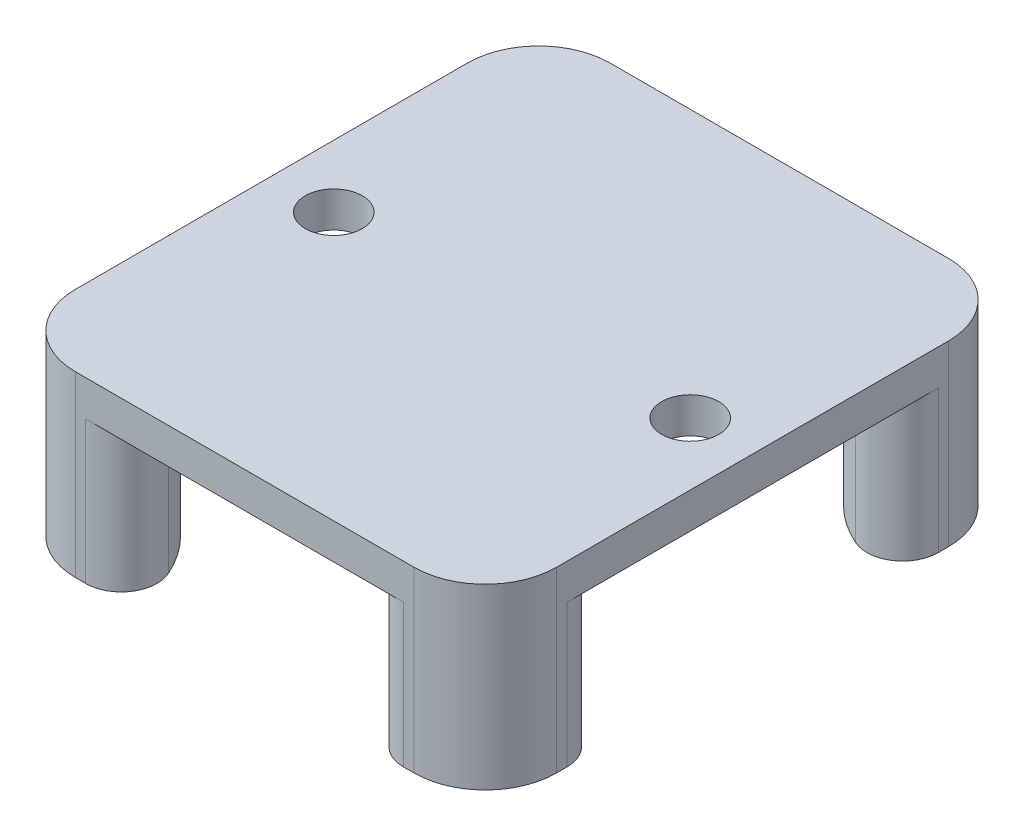
SolidWorks part; units mm, degrees
ref_plane "Płaszczyzna przednia" through (0, 0, 0) normal (0, 0, 1) x (1, 0, 0)
ref_plane "Płaszczyzna górna" through (0, 0, 0) normal (0, 1, 0) x (1, 0, 0)
ref_plane "Płaszczyzna prawa" through (0, 0, 0) normal (1, 0, 0) x (0, 0, -1)
sketch "Szkic1" plane through (0, 0, 0) normal (0, 1, 0) x (1, 0, 0)
  line L0 (-10, 0) -> (10, 0) construction
  line L2 (-13.5, -15) -> (13.5, -15)
  line L3 (-13.5, -15) -> (-13.5, 15)
  line L4 (-13.5, 15) -> (13.5, 15)
  line L5 (13.5, -15) -> (13.5, 15)
  line L6 (-13.5, -15) -> (13.5, 15) construction
  line L7 (-13.5, 15) -> (13.5, -15) construction
  circle A0 centre (10, 0) radius 1.6
  circle A1 centre (-10, 0) radius 1.6
  point P4 (0, 0)
  point P7 (0, 0)
  dimension "D1" = 3.2
  dimension "D2" = 3.2
  dimension "D3" = 27
  dimension "D4" = 30
  dimension "D5" = 20
extrude "Dodanie-wyciągnięcie1" add sketch "Szkic1" along normal blind 2
sketch "Szkic2" plane through (0, 0, 0) normal (0, -1, 0) x (1, 0, 0)
  line L0 (-13.5, 15) -> (13.5, 15) construction
  line L1 (-13.5, -15) -> (-13.5, 15) construction
  line L2 (-13.5, 8) -> (-13.5, 15)
  line L3 (-13.5, 15) -> (-6.5, 15)
  line L4 (0, -1.1) -> (0, 1.1) construction
  line L5 (13.5, 8) -> (13.5, 15)
  line L6 (13.5, 15) -> (6.5, 15)
  line L7 (1.1, 0) -> (-1.1, 0) construction
  line L8 (13.5, -15) -> (6.5, -15)
  line L9 (13.5, -8) -> (13.5, -15)
  line L10 (-13.5, -8) -> (-13.5, -15)
  line L11 (-13.5, -15) -> (-6.5, -15)
  arc A0 (-6.5, 15) -> (-13.5, 8) centre (-13.5, 15) cw
  arc A1 (6.5, 15) -> (13.5, 8) centre (13.5, 15) ccw
  arc A2 (6.5, -15) -> (13.5, -8) centre (13.5, -15) cw
  arc A3 (-6.5, -15) -> (-13.5, -8) centre (-13.5, -15) ccw
  dimension "D1" = 7
extrude "Dodanie-wyciągnięcie2" add sketch "Szkic2" along normal blind 8
fillet "Zaokrąglenie1" radius 4 4 edges at (-13.5, -3, 15) (13.5, -3, 15) (13.5, -3, -15) (-13.5, -3, -15)
fillet "Zaokrąglenie2" radius 2 8 edges at (-13.5, -4, 8) (-6.5, -4, 15) (13.5, -4, 8) (6.5, -4, 15) (-13.5, -4, -8) (-6.5, -4, -15) (13.5, -4, -8) (6.5, -4, -15)
